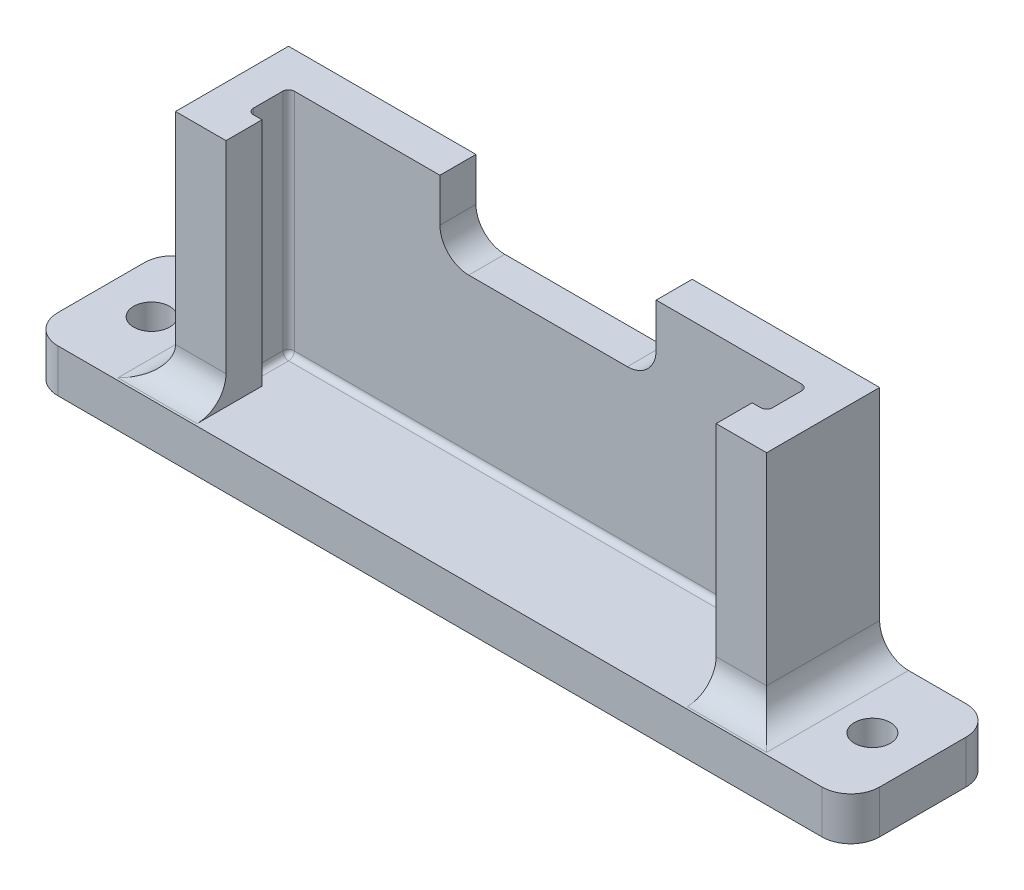
SolidWorks part; units mm, degrees
material "PLA2"
ref_plane "Front Plane" through (0, 0, 0) normal (0, 0, 1) x (1, 0, 0)
ref_plane "Top Plane" through (0, 0, 0) normal (0, 1, 0) x (1, 0, 0)
ref_plane "Right Plane" through (0, 0, 0) normal (1, 0, 0) x (0, 0, -1)
sketch "Sketch2" plane through (0, 0, 0) normal (0, 1, 0) x (1, 0, 0)
  line L0 (0, 0) -> (0, -50000) construction
  line L1 (0, 0) -> (50000, 0) construction
  line L2 (22.86, 3.6068) -> (-22.86, 3.6068)
  line L3 (-22.86, 3.6068) -> (-22.86, 0)
  line L4 (-22.86, 0) -> (-21.59, 0)
  line L5 (-21.59, 0) -> (-21.59, -3.175)
  line L6 (-21.59, -3.175) -> (-26.035, -3.175)
  line L7 (-26.035, -3.175) -> (-26.035, 6.7818)
  line L8 (-26.035, 6.7818) -> (26.035, 6.7818)
  line L9 (26.035, -3.175) -> (26.035, 6.7818)
  line L10 (21.59, -3.175) -> (26.035, -3.175)
  line L11 (21.59, 0) -> (21.59, -3.175)
  line L12 (22.86, 0) -> (21.59, 0)
  line L13 (22.86, 3.6068) -> (22.86, 0)
  point P14 (0, 6.7818)
  point P19 (0, 3.6068)
  dimension "D1" = 45.72
  dimension "D2" = 3.175
  dimension "D3" = 3.175
  dimension "D4" = 3.175
  dimension "D5" = 43.18
  dimension "D6" = 3.6068
extrude "Boss-Extrude1" add sketch "Sketch2" along normal mid plane 20.32
sketch "Sketch3" plane through (0, 0, -3.6068) normal (0, 0, 1) x (1, 0, 0)
  line L0 (0, 0) -> (0, 10.16) construction
  line L2 (-22.86, 10.16) -> (22.86, 10.16) construction
  line L3 (-9.525, 10.16) -> (-9.525, 3.81)
  line L4 (-9.525, 3.81) -> (9.525, 3.81)
  line L5 (-9.525, 10.16) -> (9.525, 10.16)
  line L6 (9.525, 10.16) -> (9.525, 3.81)
  point P10 (0, 3.81)
  dimension "D1" = 6.35
  dimension "D2" = 19.05
extrude "Cut-Extrude1" cut sketch "Sketch3" against normal blind 19.05
sketch "Sketch4" plane through (0, -10.16, 0) normal (0, -1, 0) x (1, 0, 0)
  line L0 (0, 0) -> (0, -6.7818) construction
  line L1 (26.035, -6.7818) -> (-26.035, -6.7818) construction
  line L3 (36.195, 5.9182) -> (-36.195, 5.9182)
  line L4 (-36.195, 5.9182) -> (-36.195, -6.7818)
  line L5 (-36.195, -6.7818) -> (36.195, -6.7818)
  line L6 (36.195, 5.9182) -> (36.195, -6.7818)
  point P11 (0, 5.9182)
  dimension "D1" = 12.7
  dimension "D2" = 72.39
extrude "Boss-Extrude2" add sketch "Sketch4" along normal blind 3.81
sketch "Sketch5" plane through (0, -10.16, 0) normal (0, 1, 0) x (1, 0, 0)
  line L0 (-36.195, 0.4318) -> (36.195, 0.4318) construction
  line L1 (-36.195, -5.9182) -> (-36.195, 6.7818) construction
  line L2 (36.195, 6.7818) -> (36.195, -5.9182) construction
  line L3 (0, 0) -> (0, -5.9182) construction
  line L4 (36.195, -5.9182) -> (-36.195, -5.9182) construction
  circle A0 centre (-31.75, 0.4318) radius 1.5875
  circle A1 centre (31.75, 0.4318) radius 1.5875
  dimension "D1" = 3.175
  dimension "D2" = 63.5
extrude "Cut-Extrude2" cut sketch "Sketch5" against normal through all
fillet "Fillet1" radius 2.54 4 edges at (-23.8125, -10.16, 3.175) (23.8125, -10.16, 3.175) (26.035, -10.16, -1.8034) (-26.035, -10.16, -1.8034)
fillet "Fillet2" radius 0.508 6 edges at (22.86, 0, 0) (22.86, 0, -3.6068) (0, -10.16, -3.6068) (-22.86, 0, 0) (-22.86, -10.16, -1.8034) (-22.86, 0, -3.6068)
fillet "Fillet3" radius 2.54 2 edges at (-9.525, 3.81, -5.1943) (9.525, 3.81, -5.1943)
fillet "Fillet4" radius 2.54 4 edges at (36.195, -12.065, -6.7818) (36.195, -12.065, 5.9182) (-36.195, -12.065, -6.7818) (-36.195, -12.065, 5.9182)
equation "\"D2@Sketch2\"=\"D3@Sketch2\""
equation "\"D4@Sketch2\"=\"D3@Sketch2\""
